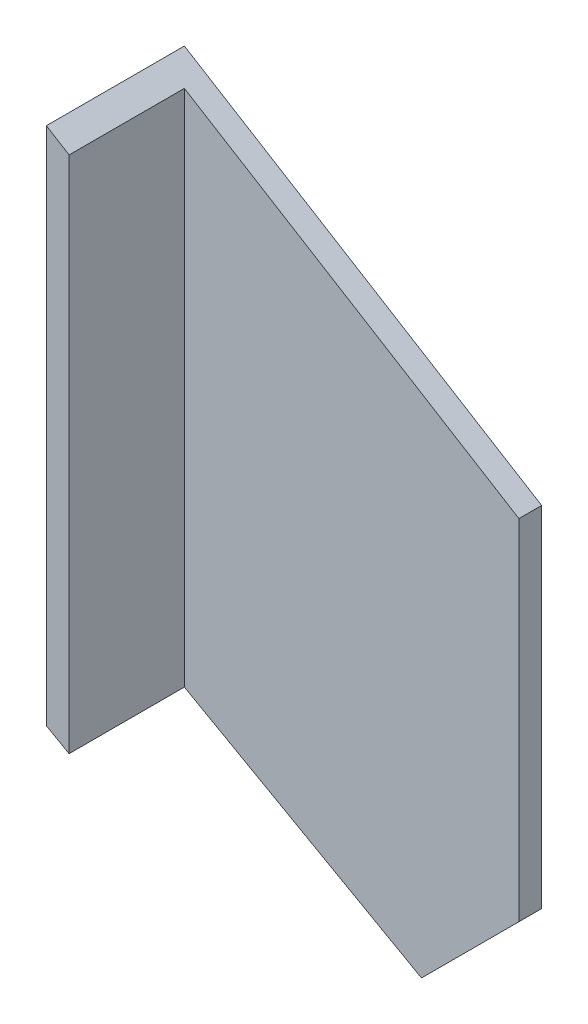
SolidWorks part; units mm, degrees
ref_plane "前视基准面" through (0, 0, 0) normal (0, 0, 1) x (1, 0, 0)
ref_plane "上视基准面" through (0, 0, 0) normal (0, 1, 0) x (1, 0, 0)
ref_plane "右视基准面" through (0, 0, 0) normal (1, 0, 0) x (0, 0, -1)
sketch "草图1" plane through (0, 0, 0) normal (0, 0, 1) x (1, 0, 0)
  line L0 (-1188.0651, 85.2964) -> (48811.9349, 85.2964) construction
  line L1 (-188.0651, -994.7583) -> (-188.0651, 49005.2417) construction
  line L2 (-1173.1343, -49.7036) -> (48826.8657, -49.7036) construction
  line L3 (-148.5651, -1041.5004) -> (-148.5651, 48958.4996) construction
  line L4 (-1169.9539, -234.7036) -> (48830.0461, -234.7036) construction
  line L5 (71.4349, -49.7036) -> (71.4349, -264.7036)
  line L6 (11.4349, -1089.7199) -> (11.4349, 48910.2801) construction
  line L7 (-972.3331, -324.7036) -> (49027.6669, -324.7036) construction
  line L8 (71.4349, -264.7036) -> (11.4349, -324.7036)
  line L9 (11.4349, -324.7036) -> (-148.5651, -234.7036)
  line L10 (-148.5651, -234.7036) -> (-148.5651, 85.2964)
  line L11 (-148.5651, 85.2964) -> (71.4349, -49.7036)
  line L12 (1811.9349, -49.7036) -> (1811.9349, -2299.7036) construction
  line L13 (1811.9349, -2299.7036) -> (-188.0651, -49.7036) construction
  point P15 (11.4349, -324.7036)
  point P17 (1811.9349, -49.7036)
  point P21 (-188.0651, -49.7036)
  dimension "D1" = 135
  dimension "D2" = 39.5
  dimension "D3" = 185
  dimension "D4" = 215
  dimension "D5" = 160
  dimension "D6" = 60
  dimension "D7" = 60
  dimension "D8" = 2000
  dimension "D9" = 2250
extrude "凸台-拉伸1" add sketch "草图1" along normal blind 14
sketch "草图2" plane through (0, 0, 14) normal (0, 0, 1) x (1, 0, 0)
  line L0 (-134.5651, 76.7055) -> (-134.5651, -242.5786)
  line L1 (71.4349, -49.7036) -> (-148.5651, 85.2964) construction
  line L2 (-148.5651, -234.7036) -> (11.4349, -324.7036) construction
  line L3 (-148.5651, 85.2964) -> (-148.5651, -234.7036) construction
  line L9 (71.4349, -49.7036) -> (-148.5651, 85.2964)
  line L10 (-148.5651, 85.2964) -> (-148.5651, -234.7036)
  line L11 (-148.5651, -234.7036) -> (11.4349, -324.7036)
  line L12 (11.4349, -324.7036) -> (71.4349, -264.7036)
  line L13 (71.4349, -264.7036) -> (71.4349, -49.7036)
  line L14 (-134.5651, 76.7055) -> (-148.5651, 85.2964)
  line L15 (-148.5651, 85.2964) -> (-148.5651, -234.7036)
  line L16 (-148.5651, -234.7036) -> (-134.5651, -242.5786)
  dimension "D1" = 14
  dimension "D2" = 0
extrude "凸台-拉伸2" add sketch "草图2" along normal blind 71
